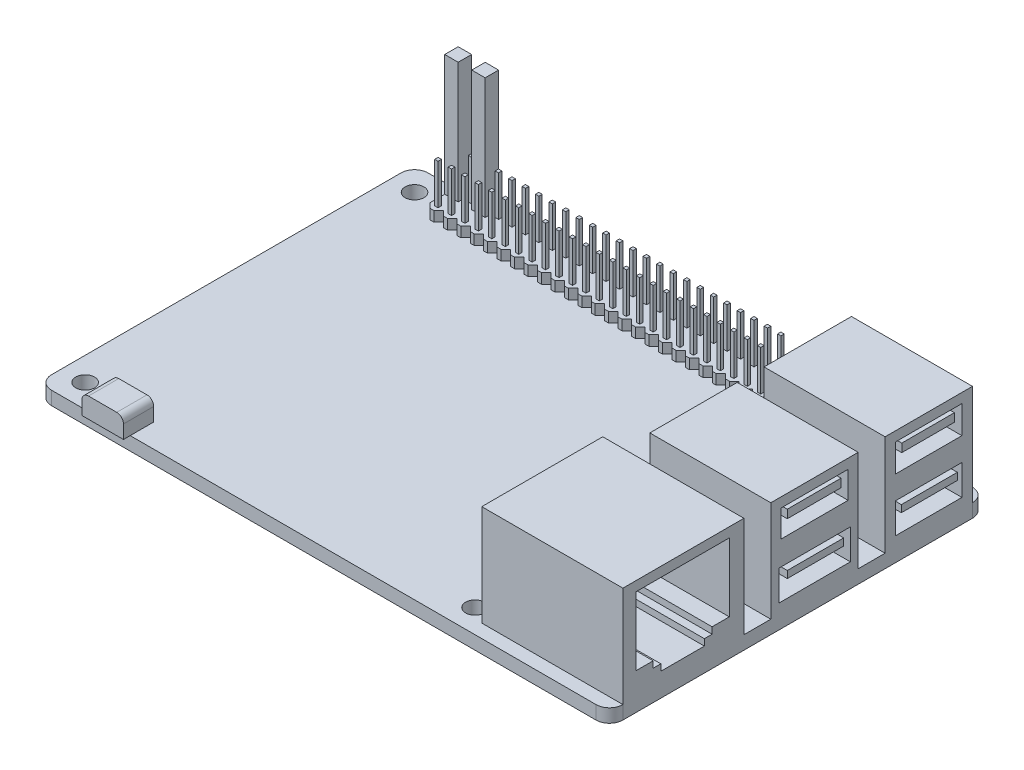
SolidWorks part; units mm, degrees
ref_plane "Front Plane" through (0, 0, 0) normal (0, 0, 1) x (1, 0, 0)
ref_plane "Top Plane" through (0, 0, 0) normal (0, 1, 0) x (1, 0, 0)
ref_plane "Right Plane" through (0, 0, 0) normal (1, 0, 0) x (0, 0, -1)
sketch "Sketch1" plane through (0, 0, 0) normal (0, 1, 0) x (1, 0, 0)
  line L0 (-55, 0) -> (55, 0) construction
  line L1 (-42.5, 28) -> (42.5, 28)
  line L2 (-42.5, 28) -> (-42.5, -28)
  line L3 (-42.5, -28) -> (42.5, -28)
  line L4 (42.5, 28) -> (42.5, -28)
  line L5 (0, -55) -> (0, 55) construction
  dimension "D1" = 56
  dimension "D2" = 28
  dimension "D3" = 85
  dimension "D4" = 42.5
extrude "Boss-Extrude1" add sketch "Sketch1" along normal blind 2
sketch "Sketch2" plane through (0, 2, 0) normal (0, 1, 0) x (1, 0, 0)
  line L0 (42.5, -28) -> (42.5, 28) construction
  line L1 (24.5, 26) -> (42.5, 26)
  line L2 (24.5, 26) -> (24.5, 13)
  line L3 (24.5, 13) -> (42.5, 13)
  line L4 (42.5, 26) -> (42.5, 13)
  line L5 (42.5, 28) -> (-42.5, 28) construction
  line L6 (24.5, 9) -> (42.5, 9)
  line L7 (24.5, 9) -> (24.5, -4)
  line L8 (24.5, -4) -> (42.5, -4)
  line L9 (42.5, 9) -> (42.5, -4)
  line L10 (21.5, -8) -> (42.5, -8)
  line L11 (21.5, -8) -> (21.5, -26)
  line L12 (21.5, -26) -> (42.5, -26)
  line L13 (42.5, -8) -> (42.5, -26)
  line L14 (-42.5, -28) -> (42.5, -28) construction
  dimension "D1" = 2
  dimension "D2" = 13
  dimension "D3" = 4
  dimension "D4" = 13
  dimension "D5" = 18
  dimension "D6" = 18
  dimension "D7" = 4
  dimension "D8" = 2
  dimension "D9" = 21
extrude "Boss-Extrude2" add sketch "Sketch2" along normal blind 15
sketch "Sketch3" plane through (42.5, 0, 0) normal (1, 0, 0) x (0, 0, -1)
  line L0 (-4, 17) -> (-4, 2) construction
  line L1 (-2.5, 15.5633) -> (7.5, 15.5633)
  line L2 (-2.5, 15.5633) -> (-2.5, 11.5633)
  line L3 (-2.5, 11.5633) -> (7.5, 11.5633)
  line L4 (7.5, 15.5633) -> (7.5, 11.5633)
  line L5 (-2.776, 7.9757) -> (7.8344, 7.9757)
  line L6 (-2.776, 7.9757) -> (-2.776, 3.4724)
  line L7 (-2.776, 3.4724) -> (7.8344, 3.4724)
  line L8 (7.8344, 7.9757) -> (7.8344, 3.4724)
  line L9 (14.5584, 15.5633) -> (24.4286, 15.5633)
  line L10 (14.5584, 15.5633) -> (14.5584, 11.4302)
  line L11 (14.5584, 11.4302) -> (24.4286, 11.4302)
  line L12 (24.4286, 15.5633) -> (24.4286, 11.4302)
  line L13 (14.5584, 7.9757) -> (24.4286, 7.9757)
  line L14 (14.5584, 7.9757) -> (14.5584, 3.4724)
  line L15 (14.5584, 3.4724) -> (24.4286, 3.4724)
  line L16 (24.4286, 7.9757) -> (24.4286, 3.4724)
  line L17 (-24.0584, 15.5633) -> (-10.1786, 15.5633)
  line L18 (-24.0584, 15.5633) -> (-24.0584, 5.3904)
  line L19 (-20.3571, 3.4724) -> (-13.8798, 3.4724)
  line L20 (-10.1786, 15.5633) -> (-10.1786, 5.3904)
  line L21 (-1.5422, 14.9464) -> (6.4578, 14.9464)
  line L22 (-1.5422, 14.9464) -> (-1.5422, 13.7127)
  line L23 (-1.5422, 13.7127) -> (6.4578, 13.7127)
  line L24 (6.4578, 14.9464) -> (6.4578, 13.7127)
  line L25 (15.4838, 14.9464) -> (23.3182, 14.9464)
  line L26 (15.4838, 14.9464) -> (15.4838, 13.7127)
  line L27 (15.4838, 13.7127) -> (23.3182, 13.7127)
  line L28 (23.3182, 14.9464) -> (23.3182, 13.7127)
  line L29 (-1.5422, 7.0503) -> (6.8474, 7.0503)
  line L30 (-1.5422, 7.0503) -> (-1.5422, 6.0016)
  line L31 (-1.5422, 6.0016) -> (6.8474, 6.0016)
  line L32 (6.8474, 7.0503) -> (6.8474, 6.0016)
  line L33 (15.4221, 7.0503) -> (23.75, 7.0503)
  line L34 (15.4221, 7.0503) -> (15.4221, 6.0016)
  line L35 (15.4221, 6.0016) -> (23.75, 6.0016)
  line L36 (23.75, 7.0503) -> (23.75, 6.0016)
  line L37 (-17.1185, 15.5633) -> (-17.1185, 3.4724) construction
  line L38 (-24.0584, 5.3904) -> (-21.5026, 5.3904)
  line L41 (-20.3571, 4.4314) -> (-20.3571, 3.4724)
  line L42 (-13.8798, 4.4314) -> (-13.8798, 3.4724)
  line L44 (-21.5026, 5.3904) -> (-21.5026, 4.4314)
  line L45 (-21.5026, 4.4314) -> (-20.3571, 4.4314)
  line L47 (-12.7343, 4.4314) -> (-13.8798, 4.4314)
  line L48 (-12.7343, 5.3904) -> (-12.7343, 4.4314)
  line L49 (-10.1786, 5.3904) -> (-12.7343, 5.3904)
  dimension "D1" = 8
  dimension "D2" = 10
  dimension "D3" = 1.5
  dimension "D4" = 4
extrude "Cut-Extrude2" cut sketch "Sketch3" against normal blind 15
sketch "Sketch4" plane through (0, 2, 0) normal (0, 1, 0) x (1, 0, 0)
  line L0 (-42.5, -28) -> (42.5, -28) construction
  line L1 (-42.5, 28) -> (-42.5, -28) construction
  line L2 (42.5, 28) -> (-42.5, 28) construction
  circle A0 centre (-39, 24.5) radius 1.4
  circle A1 centre (-39, -24.5) radius 1.4
  circle A2 centre (19, -24.5) radius 1.4
  circle A3 centre (19, 24.5) radius 1.4
  dimension "D1" = 2.8
  dimension "D2" = 2.8
  dimension "D3" = 2.8
  dimension "D4" = 2.8
  dimension "D5" = 3.5
  dimension "D6" = 3.5
  dimension "D7" = 3.5
  dimension "D8" = 3.5
  dimension "D9" = 3.5
  dimension "D10" = 3.5
  dimension "D11" = 58
  dimension "D12" = 58
extrude "Cut-Extrude3" cut sketch "Sketch4" against normal blind 15
sketch "Sketch5" plane through (0, 2, 0) normal (0, 1, 0) x (1, 0, 0)
  line L0 (-42.5, -28) -> (-31.9, -28) construction
  line L1 (-42.5, -28) -> (42.5, -28) construction
  line L3 (-35, -24.5) -> (-28.8, -24.5)
  line L4 (-35, -24.5) -> (-35, -29)
  line L5 (-35, -29) -> (-28.8, -29)
  line L6 (-28.8, -24.5) -> (-28.8, -29)
  circle A0 centre (-39, -24.5) radius 1.4 construction
  dimension "D1" = 4
  dimension "D2" = 3.1
  dimension "D3" = 3.1
  dimension "D4" = 1
  dimension "D5" = 4.5
extrude "Boss-Extrude3" add sketch "Sketch5" along normal blind 3
fillet "Fillet1" radius 1 2 edges at (-35, 5, 26.75) (-28.8, 5, 26.75)
sketch "Sketch8" plane through (0, 2, 0) normal (0, 1, 0) x (1, 0, 0)
  line L0 (-10, 27) -> (-10, 22) construction
  line L1 (-34.2929, 27) -> (-35, 26.2929)
  line L2 (-35, 26.2929) -> (-35, 22.7929)
  line L3 (-34.2929, 27) -> (-33.7071, 27)
  line L4 (-33, 26.2929) -> (-33, 22.7929)
  line L5 (-42.5, 28) -> (-42.5, -28) construction
  line L7 (-33.7071, 22.0858) -> (-34.2929, 22.0858)
  line L9 (-33.7071, 27) -> (-33, 26.2929)
  line L10 (-34.2929, 22.0858) -> (-35, 22.7929)
  line L11 (-33.7071, 22.0858) -> (-33, 22.7929)
  dimension "D1" = 32.5
  dimension "D3" = 3.5
  dimension "D4" = 1
  dimension "D8" = 1
  dimension "D10" = 1
  dimension "D12" = 1
extrude "Boss-Extrude6" add sketch "Sketch8" along normal blind 1.5
pattern_linear "LPattern1" count 25 spacing 2 along (1, 0, 0) of "Boss-Extrude6"
sketch "Sketch9" plane through (0, 3.5, 0) normal (0, 1, 0) x (1, 0, 0)
  line L0 (-35, 26.2929) -> (-35, 22.7929) construction
  line L1 (-34.25, 26.25) -> (-33.75, 26.25)
  line L2 (-34.25, 26.25) -> (-34.25, 25.75)
  line L3 (-34.25, 25.75) -> (-33.75, 25.75)
  line L4 (-33.75, 26.25) -> (-33.75, 25.75)
  line L5 (-33.7071, 27) -> (-34.2929, 27) construction
  line L6 (-32.25, 26.25) -> (-31.75, 26.25)
  line L7 (-32.25, 26.25) -> (-32.25, 25.75)
  line L8 (-31.75, 26.25) -> (-31.75, 25.75)
  line L9 (-32.25, 25.75) -> (-31.75, 25.75)
  line L10 (-30.25, 26.25) -> (-29.75, 26.25)
  line L11 (-30.25, 26.25) -> (-30.25, 25.75)
  line L12 (-29.75, 26.25) -> (-29.75, 25.75)
  line L13 (-30.25, 25.75) -> (-29.75, 25.75)
  line L14 (-28.25, 26.25) -> (-27.75, 26.25)
  line L15 (-28.25, 26.25) -> (-28.25, 25.75)
  line L16 (-27.75, 26.25) -> (-27.75, 25.75)
  line L17 (-28.25, 25.75) -> (-27.75, 25.75)
  line L18 (-26.25, 26.25) -> (-25.75, 26.25)
  line L19 (-26.25, 26.25) -> (-26.25, 25.75)
  line L20 (-25.75, 26.25) -> (-25.75, 25.75)
  line L21 (-26.25, 25.75) -> (-25.75, 25.75)
  line L22 (-24.25, 26.25) -> (-23.75, 26.25)
  line L23 (-24.25, 26.25) -> (-24.25, 25.75)
  line L24 (-23.75, 26.25) -> (-23.75, 25.75)
  line L25 (-24.25, 25.75) -> (-23.75, 25.75)
  line L26 (-22.25, 26.25) -> (-21.75, 26.25)
  line L27 (-22.25, 26.25) -> (-22.25, 25.75)
  line L28 (-21.75, 26.25) -> (-21.75, 25.75)
  line L29 (-22.25, 25.75) -> (-21.75, 25.75)
  line L30 (-20.25, 26.25) -> (-19.75, 26.25)
  line L31 (-20.25, 26.25) -> (-20.25, 25.75)
  line L32 (-19.75, 26.25) -> (-19.75, 25.75)
  line L33 (-20.25, 25.75) -> (-19.75, 25.75)
  line L34 (-18.25, 26.25) -> (-17.75, 26.25)
  line L35 (-18.25, 26.25) -> (-18.25, 25.75)
  line L36 (-17.75, 26.25) -> (-17.75, 25.75)
  line L37 (-18.25, 25.75) -> (-17.75, 25.75)
  line L38 (-16.25, 26.25) -> (-15.75, 26.25)
  line L39 (-16.25, 26.25) -> (-16.25, 25.75)
  line L40 (-15.75, 26.25) -> (-15.75, 25.75)
  line L41 (-16.25, 25.75) -> (-15.75, 25.75)
  line L42 (-14.25, 26.25) -> (-13.75, 26.25)
  line L43 (-14.25, 26.25) -> (-14.25, 25.75)
  line L44 (-13.75, 26.25) -> (-13.75, 25.75)
  line L45 (-14.25, 25.75) -> (-13.75, 25.75)
  line L46 (-12.25, 26.25) -> (-11.75, 26.25)
  line L47 (-12.25, 26.25) -> (-12.25, 25.75)
  line L48 (-11.75, 26.25) -> (-11.75, 25.75)
  line L49 (-12.25, 25.75) -> (-11.75, 25.75)
  line L50 (-10.25, 26.25) -> (-9.75, 26.25)
  line L51 (-10.25, 26.25) -> (-10.25, 25.75)
  line L52 (-9.75, 26.25) -> (-9.75, 25.75)
  line L53 (-10.25, 25.75) -> (-9.75, 25.75)
  line L54 (-8.25, 26.25) -> (-7.75, 26.25)
  line L55 (-8.25, 26.25) -> (-8.25, 25.75)
  line L56 (-7.75, 26.25) -> (-7.75, 25.75)
  line L57 (-8.25, 25.75) -> (-7.75, 25.75)
  line L58 (-6.25, 26.25) -> (-5.75, 26.25)
  line L59 (-6.25, 26.25) -> (-6.25, 25.75)
  line L60 (-5.75, 26.25) -> (-5.75, 25.75)
  line L61 (-6.25, 25.75) -> (-5.75, 25.75)
  line L62 (-4.25, 26.25) -> (-3.75, 26.25)
  line L63 (-4.25, 26.25) -> (-4.25, 25.75)
  line L64 (-3.75, 26.25) -> (-3.75, 25.75)
  line L65 (-4.25, 25.75) -> (-3.75, 25.75)
  line L66 (-2.25, 26.25) -> (-1.75, 26.25)
  line L67 (-2.25, 26.25) -> (-2.25, 25.75)
  line L68 (-1.75, 26.25) -> (-1.75, 25.75)
  line L69 (-2.25, 25.75) -> (-1.75, 25.75)
  line L70 (-0.25, 26.25) -> (0.25, 26.25)
  line L71 (-0.25, 26.25) -> (-0.25, 25.75)
  line L72 (0.25, 26.25) -> (0.25, 25.75)
  line L73 (-0.25, 25.75) -> (0.25, 25.75)
  line L74 (1.75, 26.25) -> (2.25, 26.25)
  line L75 (1.75, 26.25) -> (1.75, 25.75)
  line L76 (2.25, 26.25) -> (2.25, 25.75)
  line L77 (1.75, 25.75) -> (2.25, 25.75)
  line L78 (3.75, 26.25) -> (4.25, 26.25)
  line L79 (3.75, 26.25) -> (3.75, 25.75)
  line L80 (4.25, 26.25) -> (4.25, 25.75)
  line L81 (3.75, 25.75) -> (4.25, 25.75)
  line L82 (5.75, 26.25) -> (6.25, 26.25)
  line L83 (5.75, 26.25) -> (5.75, 25.75)
  line L84 (6.25, 26.25) -> (6.25, 25.75)
  line L85 (5.75, 25.75) -> (6.25, 25.75)
  line L86 (7.75, 26.25) -> (8.25, 26.25)
  line L87 (7.75, 26.25) -> (7.75, 25.75)
  line L88 (8.25, 26.25) -> (8.25, 25.75)
  line L89 (7.75, 25.75) -> (8.25, 25.75)
  line L90 (9.75, 26.25) -> (10.25, 26.25)
  line L91 (9.75, 26.25) -> (9.75, 25.75)
  line L92 (10.25, 26.25) -> (10.25, 25.75)
  line L93 (9.75, 25.75) -> (10.25, 25.75)
  line L94 (11.75, 26.25) -> (12.25, 26.25)
  line L95 (11.75, 26.25) -> (11.75, 25.75)
  line L96 (12.25, 26.25) -> (12.25, 25.75)
  line L97 (11.75, 25.75) -> (12.25, 25.75)
  line L98 (13.75, 26.25) -> (14.25, 26.25)
  line L99 (13.75, 26.25) -> (13.75, 25.75)
  line L100 (14.25, 26.25) -> (14.25, 25.75)
  line L101 (13.75, 25.75) -> (14.25, 25.75)
  line L102 (-32.25, 23.25) -> (-31.75, 23.25)
  line L103 (-32.25, 23.25) -> (-32.25, 22.75)
  line L104 (-31.75, 23.25) -> (-31.75, 22.75)
  line L105 (-32.25, 22.75) -> (-31.75, 22.75)
  line L106 (-30.25, 23.25) -> (-29.75, 23.25)
  line L107 (-30.25, 23.25) -> (-30.25, 22.75)
  line L108 (-29.75, 23.25) -> (-29.75, 22.75)
  line L109 (-30.25, 22.75) -> (-29.75, 22.75)
  line L110 (-28.25, 23.25) -> (-27.75, 23.25)
  line L111 (-28.25, 23.25) -> (-28.25, 22.75)
  line L112 (-27.75, 23.25) -> (-27.75, 22.75)
  line L113 (-28.25, 22.75) -> (-27.75, 22.75)
  line L114 (-26.25, 23.25) -> (-25.75, 23.25)
  line L115 (-26.25, 23.25) -> (-26.25, 22.75)
  line L116 (-25.75, 23.25) -> (-25.75, 22.75)
  line L117 (-26.25, 22.75) -> (-25.75, 22.75)
  line L118 (-24.25, 23.25) -> (-23.75, 23.25)
  line L119 (-24.25, 23.25) -> (-24.25, 22.75)
  line L120 (-23.75, 23.25) -> (-23.75, 22.75)
  line L121 (-24.25, 22.75) -> (-23.75, 22.75)
  line L122 (-22.25, 23.25) -> (-21.75, 23.25)
  line L123 (-22.25, 23.25) -> (-22.25, 22.75)
  line L124 (-21.75, 23.25) -> (-21.75, 22.75)
  line L125 (-22.25, 22.75) -> (-21.75, 22.75)
  line L126 (-20.25, 23.25) -> (-19.75, 23.25)
  line L127 (-20.25, 23.25) -> (-20.25, 22.75)
  line L128 (-19.75, 23.25) -> (-19.75, 22.75)
  line L129 (-20.25, 22.75) -> (-19.75, 22.75)
  line L130 (-18.25, 23.25) -> (-17.75, 23.25)
  line L131 (-18.25, 23.25) -> (-18.25, 22.75)
  line L132 (-17.75, 23.25) -> (-17.75, 22.75)
  line L133 (-18.25, 22.75) -> (-17.75, 22.75)
  line L134 (-16.25, 23.25) -> (-15.75, 23.25)
  line L135 (-16.25, 23.25) -> (-16.25, 22.75)
  line L136 (-15.75, 23.25) -> (-15.75, 22.75)
  line L137 (-16.25, 22.75) -> (-15.75, 22.75)
  line L138 (-14.25, 23.25) -> (-13.75, 23.25)
  line L139 (-14.25, 23.25) -> (-14.25, 22.75)
  line L140 (-13.75, 23.25) -> (-13.75, 22.75)
  line L141 (-14.25, 22.75) -> (-13.75, 22.75)
  line L142 (-12.25, 23.25) -> (-11.75, 23.25)
  line L143 (-12.25, 23.25) -> (-12.25, 22.75)
  line L144 (-11.75, 23.25) -> (-11.75, 22.75)
  line L145 (-12.25, 22.75) -> (-11.75, 22.75)
  line L146 (-10.25, 23.25) -> (-9.75, 23.25)
  line L147 (-10.25, 23.25) -> (-10.25, 22.75)
  line L148 (-9.75, 23.25) -> (-9.75, 22.75)
  line L149 (-10.25, 22.75) -> (-9.75, 22.75)
  line L150 (-8.25, 23.25) -> (-7.75, 23.25)
  line L151 (-8.25, 23.25) -> (-8.25, 22.75)
  line L152 (-7.75, 23.25) -> (-7.75, 22.75)
  line L153 (-8.25, 22.75) -> (-7.75, 22.75)
  line L154 (-6.25, 23.25) -> (-5.75, 23.25)
  line L155 (-6.25, 23.25) -> (-6.25, 22.75)
  line L156 (-5.75, 23.25) -> (-5.75, 22.75)
  line L157 (-6.25, 22.75) -> (-5.75, 22.75)
  line L158 (-4.25, 23.25) -> (-3.75, 23.25)
  line L159 (-4.25, 23.25) -> (-4.25, 22.75)
  line L160 (-3.75, 23.25) -> (-3.75, 22.75)
  line L161 (-4.25, 22.75) -> (-3.75, 22.75)
  line L162 (-2.25, 23.25) -> (-1.75, 23.25)
  line L163 (-2.25, 23.25) -> (-2.25, 22.75)
  line L164 (-1.75, 23.25) -> (-1.75, 22.75)
  line L165 (-2.25, 22.75) -> (-1.75, 22.75)
  line L166 (-0.25, 23.25) -> (0.25, 23.25)
  line L167 (-0.25, 23.25) -> (-0.25, 22.75)
  line L168 (0.25, 23.25) -> (0.25, 22.75)
  line L169 (-0.25, 22.75) -> (0.25, 22.75)
  line L170 (1.75, 23.25) -> (2.25, 23.25)
  line L171 (1.75, 23.25) -> (1.75, 22.75)
  line L172 (2.25, 23.25) -> (2.25, 22.75)
  line L173 (1.75, 22.75) -> (2.25, 22.75)
  line L174 (3.75, 23.25) -> (4.25, 23.25)
  line L175 (3.75, 23.25) -> (3.75, 22.75)
  line L176 (4.25, 23.25) -> (4.25, 22.75)
  line L177 (3.75, 22.75) -> (4.25, 22.75)
  line L178 (5.75, 23.25) -> (6.25, 23.25)
  line L179 (5.75, 23.25) -> (5.75, 22.75)
  line L180 (6.25, 23.25) -> (6.25, 22.75)
  line L181 (5.75, 22.75) -> (6.25, 22.75)
  line L182 (7.75, 23.25) -> (8.25, 23.25)
  line L183 (7.75, 23.25) -> (7.75, 22.75)
  line L184 (8.25, 23.25) -> (8.25, 22.75)
  line L185 (7.75, 22.75) -> (8.25, 22.75)
  line L186 (9.75, 23.25) -> (10.25, 23.25)
  line L187 (9.75, 23.25) -> (9.75, 22.75)
  line L188 (10.25, 23.25) -> (10.25, 22.75)
  line L189 (9.75, 22.75) -> (10.25, 22.75)
  line L190 (11.75, 23.25) -> (12.25, 23.25)
  line L191 (11.75, 23.25) -> (11.75, 22.75)
  line L192 (12.25, 23.25) -> (12.25, 22.75)
  line L193 (11.75, 22.75) -> (12.25, 22.75)
  line L194 (13.75, 23.25) -> (14.25, 23.25)
  line L195 (13.75, 23.25) -> (13.75, 22.75)
  line L196 (14.25, 23.25) -> (14.25, 22.75)
  line L197 (13.75, 22.75) -> (14.25, 22.75)
  line L198 (-34.25, 23.25) -> (-33.75, 23.25)
  line L199 (-34.25, 23.25) -> (-34.25, 22.75)
  line L200 (-33.75, 23.25) -> (-33.75, 22.75)
  line L201 (-34.25, 22.75) -> (-33.75, 22.75)
  dimension "D1" = 0.75
  dimension "D2" = 0.5
  dimension "D3" = 0.75
  dimension "D4" = 0.5
  dimension "D5" = 25
  dimension "D6" = 2
extrude "Boss-Extrude7" add sketch "Sketch9" along normal blind 6
sketch "Sketch10" plane through (0, 3.5, 0) normal (0, 1, 0) x (1, 0, 0)
  line L0 (-33.7071, 27) -> (-34.2929, 27) construction
  line L1 (-35.0078, 27) -> (-33.0078, 27)
  line L2 (-35.0078, 27) -> (-35.0078, 25)
  line L3 (-35.0078, 25) -> (-33.0078, 25)
  line L4 (-33.0078, 27) -> (-33.0078, 25)
  line L5 (-32, 27) -> (-32, 24.8358) construction
  line L6 (-31.7071, 27) -> (-32.2929, 27) construction
  line L7 (-30.9922, 27) -> (-30.9922, 25)
  line L8 (-28.9922, 25) -> (-30.9922, 25)
  line L9 (-28.9922, 27) -> (-28.9922, 25)
  line L10 (-28.9922, 27) -> (-30.9922, 27)
  dimension "D1" = 2
  dimension "D2" = 2
  dimension "D3" = 0
extrude "Boss-Extrude8" add sketch "Sketch10" along normal blind 18
fillet "Fillet2" radius 2 6 edges at (-42.5, 1, -28) (42.5, 1, -28) (42.5, 1, 28) (-42.5, 1, 28)
